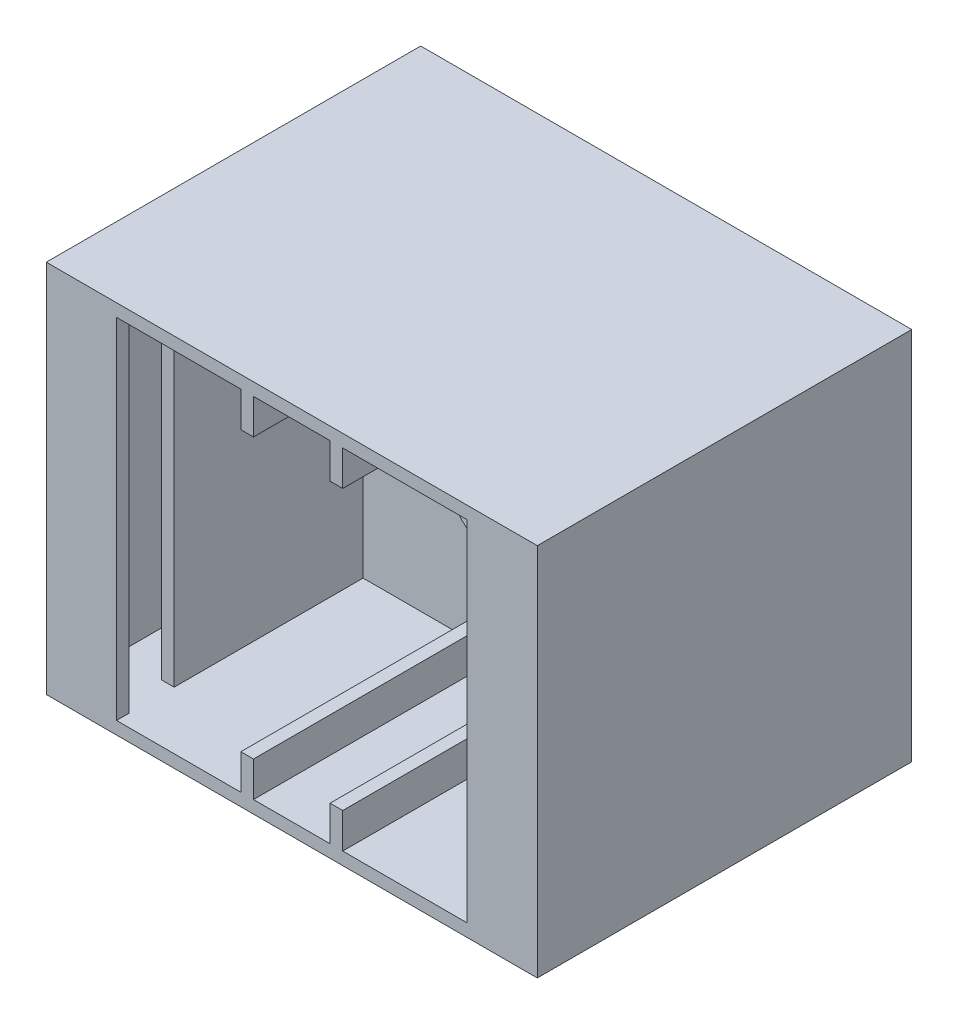
SolidWorks part; units mm, degrees
ref_plane "Front Plane" through (0, 0, 0) normal (0, 0, 1) x (1, 0, 0)
ref_plane "Top Plane" through (0, 0, 0) normal (0, 1, 0) x (1, 0, 0)
ref_plane "Right Plane" through (0, 0, 0) normal (1, 0, 0) x (0, 0, -1)
sketch "Sketch1" plane through (0, 0, 0) normal (0, 1, 0) x (1, 0, 0)
  line L0 (-331.5, 224.6725) -> (-331.5, -272.3275)
  line L1 (-349.5, 242.6725) -> (349.5, 242.6725)
  line L2 (-349.5, 242.6725) -> (-349.5, -290.3275)
  line L3 (-349.5, -290.3275) -> (-249.5, -290.3275)
  line L4 (349.5, 242.6725) -> (349.5, -290.3275)
  line L5 (-331.5, -272.3275) -> (-249.5, -272.3275)
  line L6 (331.5, 224.6725) -> (331.5, -272.3275)
  line L7 (-331.5, 224.6725) -> (331.5, 224.6725)
  line L8 (-267.5, -208.3275) -> (-267.5, 160.6725)
  line L9 (-267.5, 160.6725) -> (-72.5, 160.6725)
  line L10 (0, 684.3778) -> (0, -572.7728) construction
  line L11 (-249.5, -208.3275) -> (-249.5, 142.6725)
  line L12 (-249.5, 142.6725) -> (-72.5, 142.6725)
  line L13 (-72.5, 142.6725) -> (-72.5, 160.6725)
  line L14 (-249.5, -208.3275) -> (-267.5, -208.3275)
  line L15 (472.963, 0) -> (-779.8659, 0) construction
  line L16 (249.5, -208.3275) -> (267.5, -208.3275)
  line L17 (72.5, 142.6725) -> (72.5, 160.6725)
  line L18 (249.5, 142.6725) -> (72.5, 142.6725)
  line L19 (249.5, -208.3275) -> (249.5, 142.6725)
  line L20 (267.5, 160.6725) -> (72.5, 160.6725)
  line L21 (267.5, -208.3275) -> (267.5, 160.6725)
  line L22 (-249.5, 78.6725) -> (249.5, 78.6725)
  line L23 (9, 224.6725) -> (9, 160.6725)
  line L24 (9, 160.6725) -> (-9, 160.6725)
  line L25 (-9, 160.6725) -> (-9, 224.6725)
  line L26 (-249.5, 60.6725) -> (249.5, 60.6725)
  line L27 (-249.5, -208.3275) -> (-249.5, -282.6355) construction
  line L28 (-249.5, -272.3275) -> (-249.5, -290.3275)
  line L29 (249.5, -208.3275) -> (249.5, -285.1506) construction
  line L30 (249.5, -272.3275) -> (249.5, -290.3275)
  line L31 (249.5, -290.3275) -> (349.5, -290.3275)
  line L32 (249.5, -272.3275) -> (331.5, -272.3275)
  line L33 (-349.5, -290.3275) -> (349.5, -290.3275) construction
  line L34 (563.8617, -290.3275) -> (-696.4186, -290.3275) construction
  line L35 (-331.5, -272.3275) -> (331.5, -272.3275) construction
  point P14 (0, 242.6725)
  point P32 (0, 160.6725)
  point P35 (-249.5, -272.3275)
  point P37 (249.5, -272.3275)
  dimension "D1" = 699
  dimension "D2" = 533
  dimension "D4" = 64
  dimension "D5" = 64
  dimension "D6" = 195
  dimension "D7" = 369
  dimension "D9" = 64
  dimension "D10" = 64
  dimension "D11" = 18
  dimension "D13" = 60.6725
  dimension "D14" = 322.5
  dimension "D3" = 18
  dimension "D8" = 18
  dimension "D12" = 18
extrude "Boss-Extrude1" add sketch "Sketch1" along normal blind 515 contours L32 L30 L31 L4 L1 L2 L3 L28 L5 L0 L7 L6 | L16 L21 L20 L17 L18 L19 | L11 L26 L19 L22 | L25 L24 L23 L7 | L14 L11 L12 L13 L9 L8
sketch "Sketch4" plane through (0, 0, 0) normal (0, 1, 0) x (1, 0, 0)
  line L1 (349.5, -290.3275) -> (-349.5, -290.3275)
  line L2 (349.5, -290.3275) -> (349.5, 242.6725)
  line L3 (349.5, 242.6725) -> (-349.5, 242.6725)
  line L4 (-349.5, -290.3275) -> (-349.5, 242.6725)
extrude "Boss-Extrude2" add sketch "Sketch4" along normal blind 18
sketch "Sketch5" plane through (0, 515, 0) normal (0, 1, 0) x (1, 0, 0)
  line L1 (-349.5, -290.3275) -> (349.5, -290.3275)
  line L2 (-349.5, -290.3275) -> (-349.5, 242.6725)
  line L3 (-349.5, 242.6725) -> (349.5, 242.6725)
  line L4 (349.5, -290.3275) -> (349.5, 242.6725)
extrude "Boss-Extrude3" add sketch "Sketch5" along normal blind 18
sketch "Sketch7" plane through (0, 18, 0) normal (0, 1, 0) x (1, 0, 0)
  line L0 (72.5, -290.3275) -> (72.5, 60.6725)
  line L1 (0, -481.661) -> (0, 333.2281) construction
  line L2 (367.0603, -290.3275) -> (-515.9877, -290.3275) construction
  line L3 (104.6699, 60.6725) -> (-120.5162, 60.6725) construction
  line L4 (-249.5, 60.6725) -> (249.5, 60.6725) construction
  line L5 (-72.5, -290.3275) -> (-72.5, 60.6725)
  line L6 (-349.5, 242.6725) -> (-349.5, -290.3275) construction
  line L7 (54.5, -290.3275) -> (54.5, 60.6725)
  line L8 (-54.5, -290.3275) -> (-54.5, 60.6725)
  line L9 (72.5, 60.6725) -> (54.5, 60.6725)
  line L10 (-54.5, 60.6725) -> (-72.5, 60.6725)
  line L11 (72.5, -290.3275) -> (54.5, -290.3275)
  line L12 (-54.5, -290.3275) -> (-72.5, -290.3275)
  dimension "D1" = 277
  dimension "D2" = 277
  dimension "D3" = 18
  dimension "D4" = 18
extrude "Boss-Extrude4" add sketch "Sketch7" along normal blind 50
sketch "Sketch8" plane through (0, 515, 0) normal (0, -1, 0) x (1, 0, 0)
  line L0 (-72.5, 290.3275) -> (-72.5, -60.6725)
  line L1 (-72.5, -60.6725) -> (-54.5, -60.6725)
  line L2 (-54.5, -60.6725) -> (-54.5, 290.3275)
  line L3 (-54.5, 290.3275) -> (-72.5, 290.3275)
  line L4 (0, 415.0065) -> (0, -122.8344) construction
  line L5 (54.5, 290.3275) -> (72.5, 290.3275)
  line L6 (54.5, -60.6725) -> (54.5, 290.3275)
  line L7 (72.5, -60.6725) -> (54.5, -60.6725)
  line L8 (72.5, 290.3275) -> (72.5, -60.6725)
extrude "Boss-Extrude5" add sketch "Sketch8" along normal blind 50
sketch "Sketch9" plane through (0, 0, -60.6725) normal (0, 0, 1) x (1, 0, 0)
  line L0 (0, 629.87) -> (0, -123.9591) construction
  line L1 (-502.1012, 266.5) -> (589.1112, 266.5) construction
  line L3 (-349.5, 533) -> (-349.5, 0) construction
  line L5 (-349.5, 533) -> (349.5, 533) construction
  circle A0 centre (0, 266.5) radius 152.5
  point P7 (-349.5, 266.5)
  point P8 (0, 266.5)
  point P11 (0, 0)
  point P14 (0, 419)
  dimension "D1" = 305
  dimension "D2" = 114
extrude "Cut-Extrude1" cut sketch "Sketch9" against normal blind 50
equation "\"´699\"=69.7769"
